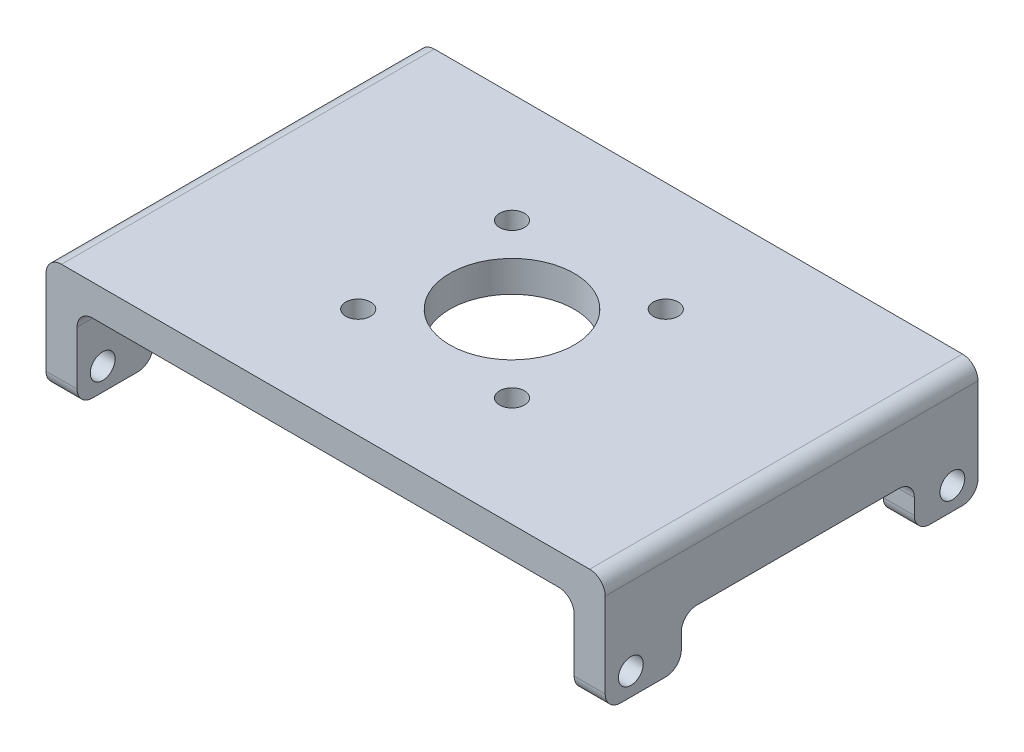
SolidWorks part; units mm, degrees
ref_plane "前视基准面" through (0, 0, 0) normal (0, 0, 1) x (1, 0, 0)
ref_plane "上视基准面" through (0, 0, 0) normal (0, 1, 0) x (1, 0, 0)
ref_plane "右视基准面" through (0, 0, 0) normal (1, 0, 0) x (0, 0, -1)
sketch "草图1" plane through (0, 0, 0) normal (0, 0, 1) x (1, 0, 0)
  line L0 (-18, 0) -> (18, 0)
  line L1 (18, 0) -> (18, -9.4552)
  line L2 (18, -9.4552) -> (16, -9.4552)
  line L3 (16, -9.4552) -> (16, -2)
  line L4 (16, -2) -> (-16, -2)
  line L5 (-16, -2) -> (-16, -8.5735)
  line L6 (-16, -8.5735) -> (-18, -8.5735)
  line L7 (-18, -8.5735) -> (-18, 0)
  dimension "D1" = 32
  dimension "D2" = 16
  dimension "D3" = 36
  dimension "D4" = 2
  dimension "D5" = 2
extrude "凸台-拉伸1" add sketch "草图1" along normal blind 32
fillet "圆角1" radius 1 4 edges at (-18, 0, 16) (-16, -2, 16) (16, -2, 16) (18, 0, 16)
sketch "草图2" plane through (18, 0, 0) normal (1, 0, 0) x (0, 0, -1)
  line L1 (0, -9.4552) -> (0, -1) construction
  line L3 (-32, 0) -> (0, 0) construction
  circle A0 centre (-26.35, -6) radius 0.8
  circle A1 centre (-5.65, -6) radius 0.8
  dimension "D1" = 1.6
  dimension "D2" = 1.6
  dimension "D3" = 20.7
  dimension "D4" = 5.65
  dimension "D5" = 6
extrude "切除-拉伸1" cut sketch "草图2" against normal through all
sketch "草图3" plane through (0, 0, 32) normal (0, 0, 1) x (1, 0, 0)
  line L1 (-21.9694, 5.034) -> (21.8779, 5.034)
  line L2 (-21.9694, 5.034) -> (-21.9694, -13.1633)
  line L3 (-21.9694, -13.1633) -> (21.8779, -13.1633)
  line L4 (21.8779, 5.034) -> (21.8779, -13.1633)
extrude "切除-拉伸2" cut sketch "草图3" against normal blind 4
sketch "草图4" plane through (0, 0, 0) normal (0, 0, -1) x (-1, 0, 0)
  line L1 (-23.1124, 5.3083) -> (24.7127, 5.3083)
  line L2 (-23.1124, 5.3083) -> (-23.1124, -11.9288)
  line L3 (-23.1124, -11.9288) -> (24.7127, -11.9288)
  line L4 (24.7127, 5.3083) -> (24.7127, -11.9288)
extrude "切除-拉伸3" cut sketch "草图4" against normal blind 4
sketch "草图5" plane through (0, -9.4552, 0) normal (0, -1, 0) x (1, 0, 0)
  line L1 (-19.4814, 29.6209) -> (20.8549, 29.6209)
  line L2 (-19.4814, 29.6209) -> (-19.4814, 2.4706)
  line L3 (-19.4814, 2.4706) -> (20.8549, 2.4706)
  line L4 (20.8549, 29.6209) -> (20.8549, 2.4706)
extrude "切除-拉伸4" cut sketch "草图5" against normal blind 2
sketch "草图6" plane through (18, 0, 0) normal (1, 0, 0) x (0, 0, -1)
  line L0 (-4, -7.4552) -> (-28, -7.4552) construction
  line L1 (-23.1, -7.4552) -> (-8.1, -7.4552)
  line L2 (-23.1, -7.4552) -> (-23.1, -4.4552)
  line L3 (-23.1, -4.4552) -> (-8.1, -4.4552)
  line L4 (-8.1, -7.4552) -> (-8.1, -4.4552)
  circle A0 centre (-26.35, -6) radius 0.8 construction
  dimension "D1" = 3
  dimension "D2" = 15
  dimension "D3" = 3.25
extrude "切除-拉伸5" cut sketch "草图6" against normal through all
fillet "圆角2" radius 1 12 edges at (-17, -4.4552, 23.1) (-17, -7.4552, 23.1) (-17, -7.4552, 28) (-17, -4.4552, 8.1) (-17, -7.4552, 8.1) (-17, -7.4552, 4) (17, -7.4552, 4) (17, -7.4552, 8.1) (17, -4.4552, 8.1) (17, -7.4552, 28) (17, -4.4552, 23.1) (17, -7.4552, 23.1)
sketch "草图7" plane through (0, 0, 0) normal (0, 1, 0) x (1, 0, 0)
  line L0 (0, -5.7671) -> (0, -25.2256) construction
  line L1 (6.8266, -9.1734) -> (0, -16) construction
  circle A0 centre (0, -16) radius 4
  circle A1 centre (0, -16) radius 7 construction
  circle A2 centre (4.9497, -11.0503) radius 0.8
  circle A3 centre (4.9497, -20.9497) radius 0.8
  circle A4 centre (-4.9497, -20.9497) radius 0.8
  circle A5 centre (-4.9497, -11.0503) radius 0.8
  point P7 (4.9497, -11.0503)
  point P19 (0, -16)
  dimension "D1" = 45
  dimension "D2" = 4
  dimension "D3" = 14
extrude "切除-拉伸6" cut sketch "草图7" against normal blind 2
